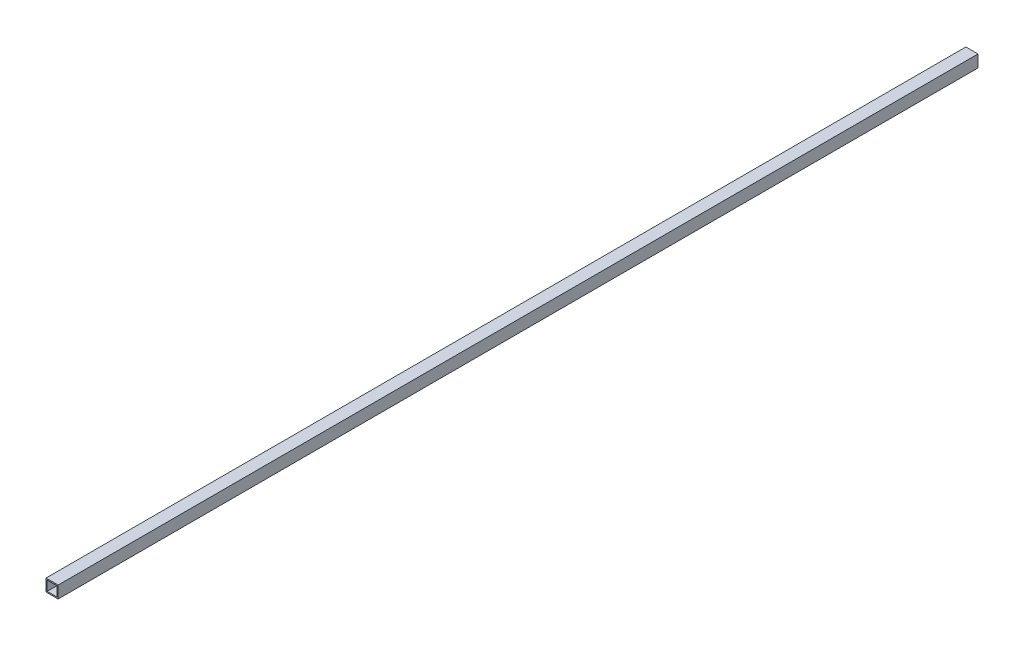
SolidWorks part; units mm, degrees
material "Thornel Mat VMA"
ref_plane "Front Plane" through (0, 0, 0) normal (0, 0, 1) x (1, 0, 0)
ref_plane "Top Plane" through (0, 0, 0) normal (0, 1, 0) x (1, 0, 0)
ref_plane "Right Plane" through (0, 0, 0) normal (1, 0, 0) x (0, 0, -1)
sketch "Sketch1" plane through (0, 0, 0) normal (0, 0, 1) x (1, 0, 0)
  line L0 (-5.15, -5.15) -> (-5.15, 5.15)
  line L1 (-4.15, -4.15) -> (4.15, -4.15)
  line L2 (-4.15, -4.15) -> (-4.15, 4.15)
  line L3 (-4.15, 4.15) -> (4.15, 4.15)
  line L4 (4.15, -4.15) -> (4.15, 4.15)
  line L5 (-4.15, -4.15) -> (4.15, 4.15) construction
  line L6 (-4.15, 4.15) -> (4.15, -4.15) construction
  line L7 (-5.15, 5.15) -> (5.15, 5.15)
  line L8 (5.15, -5.15) -> (5.15, 5.15)
  line L9 (-5.15, -5.15) -> (5.15, -5.15)
  point P10 (0, 0)
  dimension "D1" = 1
  dimension "D2" = 10.3
  dimension "D3" = 10.3
extrude "Boss-Extrude1" add sketch "Sketch1" along normal blind 781
equation "\"D1@Boss-Extrude1\"=781"
